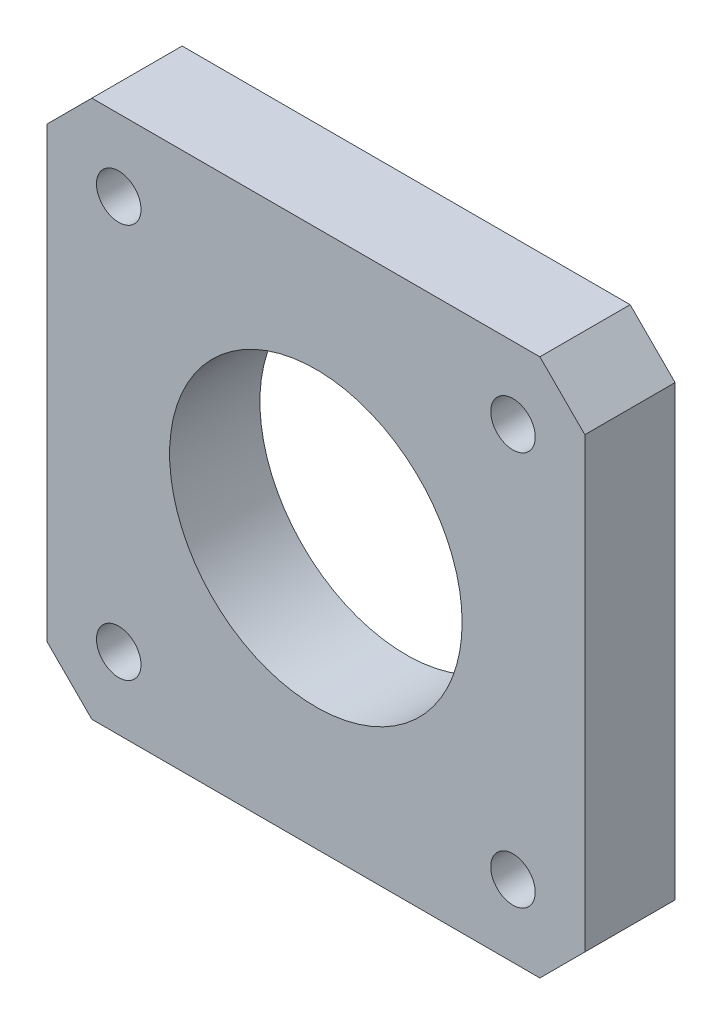
SolidWorks part; units mm, degrees
material "PLA"
ref_plane "Front Plane" through (0, 0, 0) normal (0, 0, 1) x (1, 0, 0)
ref_plane "Top Plane" through (0, 0, 0) normal (0, 1, 0) x (1, 0, 0)
ref_plane "Right Plane" through (0, 0, 0) normal (1, 0, 0) x (0, 0, -1)
sketch "Sketch1" plane through (0, 0, 0) normal (0, 0, 1) x (1, 0, 0)
  line L0 (21.15, -17.6145) -> (21.15, 17.6145)
  line L1 (21.15, 17.6145) -> (17.6145, 21.15)
  line L2 (17.6145, 21.15) -> (-17.6145, 21.15)
  line L3 (-17.6145, 21.15) -> (-21.15, 17.6145)
  line L4 (-21.15, 17.6145) -> (-21.15, -17.6145)
  line L5 (-21.15, -17.6145) -> (-17.6145, -21.15)
  line L6 (-17.6145, -21.15) -> (17.6145, -21.15)
  line L7 (17.6145, -21.15) -> (21.15, -17.6145)
  line L9 (-15.5, -15.5) -> (15.5, -15.5) construction
  line L10 (-15.5, -15.5) -> (-15.5, 15.5) construction
  line L11 (-15.5, 15.5) -> (15.5, 15.5) construction
  line L12 (15.5, -15.5) -> (15.5, 15.5) construction
  line L13 (-15.5, -15.5) -> (15.5, 15.5) construction
  line L14 (-15.5, 15.5) -> (15.5, -15.5) construction
  circle A0 centre (-15.5, 15.5) radius 1.75
  circle A1 centre (15.5, 15.5) radius 1.75
  circle A2 centre (15.5, -15.5) radius 1.75
  circle A3 centre (-15.5, -15.5) radius 1.75
  circle A4 centre (0, 0) radius 11.5
  point P2 (0, 21.15)
  point P9 (-21.15, 0)
  point P14 (0, 0)
  dimension "D2" = 3.5
  dimension "D6" = 23
  dimension "D1" = 42.3
  dimension "D3" = 31
  dimension "D4" = 31
  dimension "D5" = 5
extrude "Boss-Extrude1" add sketch "Sketch1" along normal mid plane 7.1
